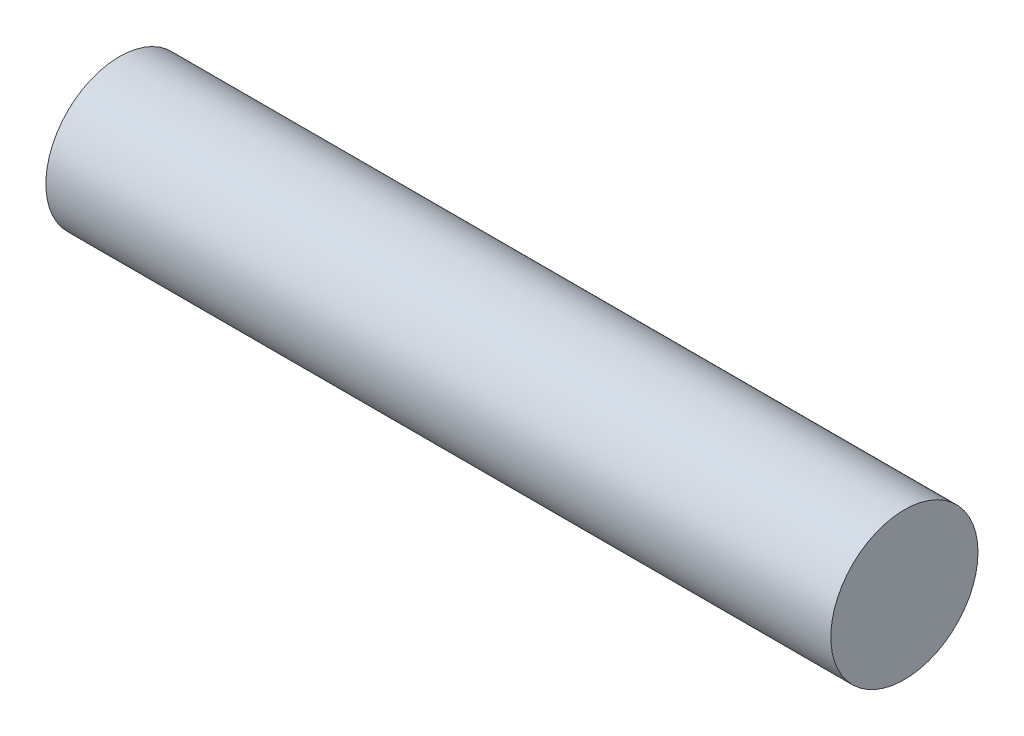
SolidWorks part; units mm, degrees
material "AISI 4130 Steel, annealed at 865C"
ref_plane "X-Y Datum" through (0, 0, 0) normal (0, 0, 1) x (1, 0, 0)
ref_plane "X-Z Datum" through (0, 0, 0) normal (0, 1, 0) x (1, 0, 0)
ref_plane "Y-Z Datum" through (0, 0, 0) normal (1, 0, 0) x (0, 0, -1)
sketch "Sketch1" plane through (0, 0, 0) normal (0, 1, 0) x (1, 0, 0)
  line L0 (139.925, 9.525) -> (139.925, 7.9375)
  line L1 (139.925, 7.9375) -> (19.25, 7.9375)
  line L2 (19.25, 7.9375) -> (19.25, 9.525)
  line L3 (19.25, 9.525) -> (139.925, 9.525)
  line L6 (157.324, 0) -> (-11.2643, 0) construction
  line L7 (19.25, 9.525) -> (19.25, -9.525) construction
  dimension "D1" = 1.5875
revolve "Revolve1" add sketch "Sketch1" angle 360 about L6
sketch "Sketch4" plane through (0, 0, 0) normal (1, 0, 0) x (0, 0, -1)
  line L0 (-9.2357, 0.808) -> (-8.6817, 0.254)
  line L1 (-8.6817, 0.254) -> (-8.6817, -0.254)
  line L2 (-8.6817, -0.254) -> (-9.2357, -0.808)
  line L3 (-8.6817, 0) -> (0, 0) construction
  line L4 (-8.5939, 1.2574) -> (-9.2357, 0.808)
  line L5 (-8.5057, 1.7577) -> (-8.5939, 1.2574)
  line L6 (-8.9551, 2.3995) -> (-8.5057, 1.7577)
  line L7 (-8.245, 2.7306) -> (-8.9551, 2.3995)
  line L8 (-8.0713, 3.208) -> (-8.245, 2.7306)
  line L9 (-8.4024, 3.9181) -> (-8.0713, 3.208)
  line L10 (-7.6456, 4.1209) -> (-8.4024, 3.9181)
  line L11 (-7.3916, 4.5608) -> (-7.6456, 4.1209)
  line L12 (-7.5944, 5.3176) -> (-7.3916, 4.5608)
  line L13 (-6.8138, 5.3859) -> (-7.5944, 5.3176)
  line L14 (-6.4873, 5.7751) -> (-6.8138, 5.3859)
  line L15 (-6.5556, 6.5556) -> (-6.4873, 5.7751)
  line L16 (-5.7751, 6.4873) -> (-6.5556, 6.5556)
  line L17 (-5.3859, 6.8138) -> (-5.7751, 6.4873)
  line L18 (-5.3176, 7.5944) -> (-5.3859, 6.8138)
  line L19 (-4.5608, 7.3916) -> (-5.3176, 7.5944)
  line L20 (-4.1209, 7.6456) -> (-4.5608, 7.3916)
  line L21 (-3.9181, 8.4024) -> (-4.1209, 7.6456)
  line L22 (-3.208, 8.0713) -> (-3.9181, 8.4024)
  line L23 (-2.7306, 8.245) -> (-3.208, 8.0713)
  line L24 (-2.3995, 8.9551) -> (-2.7306, 8.245)
  line L25 (-1.7577, 8.5057) -> (-2.3995, 8.9551)
  line L26 (-1.2574, 8.5939) -> (-1.7577, 8.5057)
  line L27 (-0.808, 9.2357) -> (-1.2574, 8.5939)
  line L28 (-0.254, 8.6817) -> (-0.808, 9.2357)
  line L29 (0.254, 8.6817) -> (-0.254, 8.6817)
  line L30 (0.808, 9.2357) -> (0.254, 8.6817)
  line L31 (1.2574, 8.5939) -> (0.808, 9.2357)
  line L32 (1.7577, 8.5057) -> (1.2574, 8.5939)
  line L33 (2.3995, 8.9551) -> (1.7577, 8.5057)
  line L34 (2.7306, 8.245) -> (2.3995, 8.9551)
  line L35 (3.208, 8.0713) -> (2.7306, 8.245)
  line L36 (3.9181, 8.4024) -> (3.208, 8.0713)
  line L37 (4.1209, 7.6456) -> (3.9181, 8.4024)
  line L38 (4.5608, 7.3916) -> (4.1209, 7.6456)
  line L39 (5.3176, 7.5944) -> (4.5608, 7.3916)
  line L40 (5.3859, 6.8138) -> (5.3176, 7.5944)
  line L41 (5.7751, 6.4873) -> (5.3859, 6.8138)
  line L42 (6.5556, 6.5556) -> (5.7751, 6.4873)
  line L43 (6.4873, 5.7751) -> (6.5556, 6.5556)
  line L44 (6.8138, 5.3859) -> (6.4873, 5.7751)
  line L45 (7.5944, 5.3176) -> (6.8138, 5.3859)
  line L46 (7.3916, 4.5608) -> (7.5944, 5.3176)
  line L47 (7.6456, 4.1209) -> (7.3916, 4.5608)
  line L48 (8.4024, 3.9181) -> (7.6456, 4.1209)
  line L49 (8.0713, 3.208) -> (8.4024, 3.9181)
  line L50 (8.245, 2.7306) -> (8.0713, 3.208)
  line L51 (8.9551, 2.3995) -> (8.245, 2.7306)
  line L52 (8.5057, 1.7577) -> (8.9551, 2.3995)
  line L53 (8.5939, 1.2574) -> (8.5057, 1.7577)
  line L54 (9.2357, 0.808) -> (8.5939, 1.2574)
  line L55 (8.6817, 0.254) -> (9.2357, 0.808)
  line L56 (8.6817, -0.254) -> (8.6817, 0.254)
  line L57 (9.2357, -0.808) -> (8.6817, -0.254)
  line L58 (8.5939, -1.2574) -> (9.2357, -0.808)
  line L59 (8.5057, -1.7577) -> (8.5939, -1.2574)
  line L60 (8.9551, -2.3995) -> (8.5057, -1.7577)
  line L61 (8.245, -2.7306) -> (8.9551, -2.3995)
  line L62 (8.0713, -3.208) -> (8.245, -2.7306)
  line L63 (8.4024, -3.9181) -> (8.0713, -3.208)
  line L64 (7.6456, -4.1209) -> (8.4024, -3.9181)
  line L65 (7.3916, -4.5608) -> (7.6456, -4.1209)
  line L66 (7.5944, -5.3176) -> (7.3916, -4.5608)
  line L67 (6.8138, -5.3859) -> (7.5944, -5.3176)
  line L68 (6.4873, -5.7751) -> (6.8138, -5.3859)
  line L69 (6.5556, -6.5556) -> (6.4873, -5.7751)
  line L70 (5.7751, -6.4873) -> (6.5556, -6.5556)
  line L71 (5.3859, -6.8138) -> (5.7751, -6.4873)
  line L72 (5.3176, -7.5944) -> (5.3859, -6.8138)
  line L73 (4.5608, -7.3916) -> (5.3176, -7.5944)
  line L74 (4.1209, -7.6456) -> (4.5608, -7.3916)
  line L75 (3.9181, -8.4024) -> (4.1209, -7.6456)
  line L76 (3.208, -8.0713) -> (3.9181, -8.4024)
  line L77 (2.7306, -8.245) -> (3.208, -8.0713)
  line L78 (2.3995, -8.9551) -> (2.7306, -8.245)
  line L79 (1.7577, -8.5057) -> (2.3995, -8.9551)
  line L80 (1.2574, -8.5939) -> (1.7577, -8.5057)
  line L81 (0.808, -9.2357) -> (1.2574, -8.5939)
  line L82 (0.254, -8.6817) -> (0.808, -9.2357)
  line L83 (-0.254, -8.6817) -> (0.254, -8.6817)
  line L84 (-0.808, -9.2357) -> (-0.254, -8.6817)
  line L85 (-1.2574, -8.5939) -> (-0.808, -9.2357)
  line L86 (-1.7577, -8.5057) -> (-1.2574, -8.5939)
  line L87 (-2.3995, -8.9551) -> (-1.7577, -8.5057)
  line L88 (-2.7306, -8.245) -> (-2.3995, -8.9551)
  line L89 (-3.208, -8.0713) -> (-2.7306, -8.245)
  line L90 (-3.9181, -8.4024) -> (-3.208, -8.0713)
  line L91 (-4.1209, -7.6456) -> (-3.9181, -8.4024)
  line L92 (-4.5608, -7.3916) -> (-4.1209, -7.6456)
  line L93 (-5.3176, -7.5944) -> (-4.5608, -7.3916)
  line L94 (-5.3859, -6.8138) -> (-5.3176, -7.5944)
  line L95 (-5.7751, -6.4873) -> (-5.3859, -6.8138)
  line L96 (-6.5556, -6.5556) -> (-5.7751, -6.4873)
  line L97 (-6.4873, -5.7751) -> (-6.5556, -6.5556)
  line L98 (-6.8138, -5.3859) -> (-6.4873, -5.7751)
  line L99 (-7.5944, -5.3176) -> (-6.8138, -5.3859)
  line L100 (-7.3916, -4.5608) -> (-7.5944, -5.3176)
  line L101 (-7.6456, -4.1209) -> (-7.3916, -4.5608)
  line L102 (-8.4024, -3.9181) -> (-7.6456, -4.1209)
  line L103 (-8.0713, -3.208) -> (-8.4024, -3.9181)
  line L104 (-8.245, -2.7306) -> (-8.0713, -3.208)
  line L105 (-8.9551, -2.3995) -> (-8.245, -2.7306)
  line L106 (-8.5057, -1.7577) -> (-8.9551, -2.3995)
  line L107 (-8.5939, -1.2574) -> (-8.5057, -1.7577)
  line L108 (-9.2357, -0.808) -> (-8.5939, -1.2574)
  circle A0 centre (0, 0) radius 8.6854 construction
  circle A1 centre (0, 0) radius 9.271 construction
  circle A2 centre (0, 0) radius 12.7
  point P155 (0, 0)
  dimension "D1" = 18.542
  dimension "D2" = 0.508
  dimension "D3" = 17.3708
  dimension "D6" = 25.4
  dimension "D4" = 135
  dimension "D5" = 1.616
  dimension "D7" = 36
sketch "Sketch6" plane through (19.25, 0, 0) normal (-1, 0, 0) x (0, 0, 1)
  circle A0 centre (0, 0) radius 7.9375
  dimension "D1" = 15.875
extrude "Boss-Extrude1" add sketch "Sketch6" against normal blind 101.6
sketch "Sketch7" plane through (120.85, 0, 0) normal (1, 0, 0) x (0, 0, -1)
  circle A0 centre (0, 0) radius 23.308
extrude "Cut-Extrude3" cut sketch "Sketch7" along normal up to surface (19.075 mm away) up to face at (139.925, 0, -9.525)
